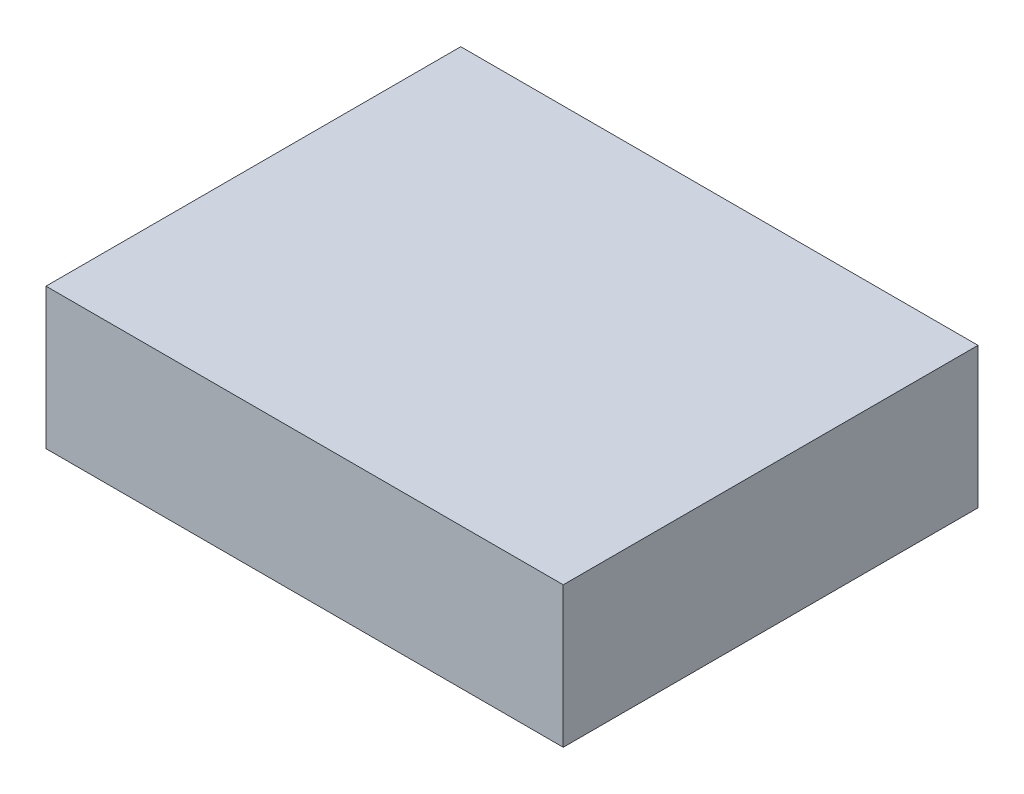
SolidWorks part; units mm, degrees
ref_plane "前基準面" through (0, 0, 0) normal (0, 0, 1) x (1, 0, 0)
ref_plane "上基準面" through (0, 0, 0) normal (0, 1, 0) x (1, 0, 0)
ref_plane "右基準面" through (0, 0, 0) normal (1, 0, 0) x (0, 0, -1)
sketch "草圖1" plane through (0, 0, 0) normal (0, 1, 0) x (1, 0, 0)
  line L1 (-37.85, 30.35) -> (37.85, 30.35)
  line L2 (-37.85, 30.35) -> (-37.85, -30.35)
  line L3 (-37.85, -30.35) -> (37.85, -30.35)
  line L4 (37.85, 30.35) -> (37.85, -30.35)
  line L5 (-37.85, 30.35) -> (37.85, -30.35) construction
  line L6 (-37.85, -30.35) -> (37.85, 30.35) construction
  point P0 (0, 0)
  dimension "D1" = 75.7
  dimension "D2" = 60.7
extrude "填料-伸長1" add sketch "草圖1" along normal blind 20.6
